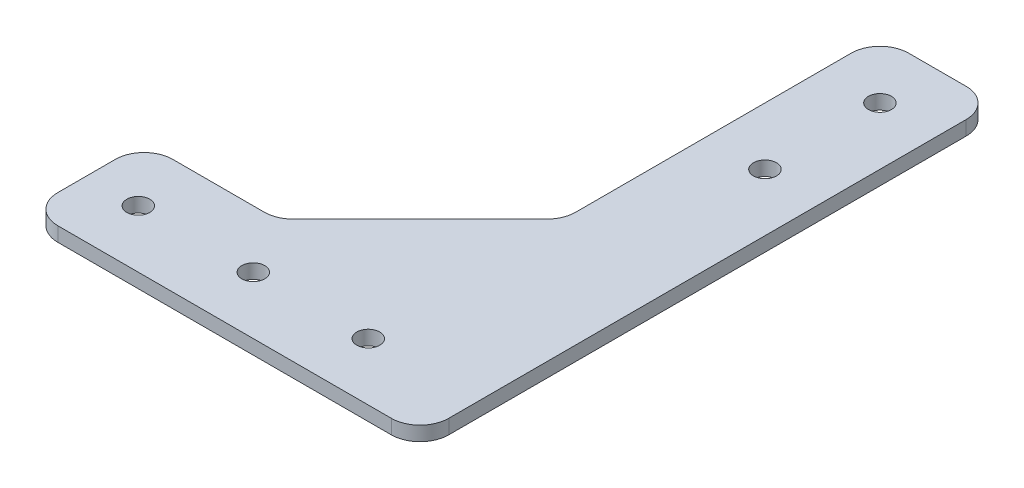
SolidWorks part; units mm, degrees
ref_plane "Front Plane" through (0, 0, 0) normal (0, 0, 1) x (1, 0, 0)
ref_plane "Top Plane" through (0, 0, 0) normal (0, 1, 0) x (1, 0, 0)
ref_plane "Right Plane" through (0, 0, 0) normal (1, 0, 0) x (0, 0, -1)
sketch "Sketch1" plane through (0, 0, 0) normal (0, 1, 0) x (1, 0, 0)
  line L0 (0, -101.6) -> (0, 0)
  line L1 (0, 0) -> (25.4, 0)
  line L2 (0, 0) -> (0, -127) construction
  line L3 (0, -127) -> (25.4, -127)
  line L4 (25.4, 0) -> (25.4, -127)
  line L5 (25.4, -127) -> (-60.96, -127)
  line L6 (25.4, -127) -> (25.4, -101.6)
  line L7 (25.4, -101.6) -> (-60.96, -101.6)
  line L8 (-60.96, -127) -> (-60.96, -101.6)
  line L9 (12.7, 0) -> (12.7, -127) construction
  line L10 (-60.96, -114.3) -> (25.4, -114.3) construction
  line L11 (-49.53, -114.3) -> (-24.13, -114.3) construction
  circle A0 centre (12.7, -12.7) radius 2.54
  circle A1 centre (12.7, -38.1) radius 2.54
  circle A4 centre (-49.53, -114.3) radius 2.54
  circle A7 centre (-24.13, -114.3) radius 2.54
  circle A8 centre (1.27, -114.3) radius 2.54
  circle A10 centre (26.67, -114.3) radius 2.54 [skipped]
  dimension "D9" = 5.08
  dimension "D12" = 5.08
  dimension "D1" = 25.4
  dimension "D2" = 25.4
  dimension "D3" = 127
  dimension "D4" = 86.36
  dimension "D5" = 11.43
  dimension "D6" = 25.4
  dimension "D7" = 12.7
  dimension "D11" = 25.4
  dimension "D10" = 4
extrude "Boss-Extrude1" add sketch "Sketch1" along normal blind 3.175
chamfer "Chamfer1" distance 31.75 angle 45 1 edges at (0, 1.5875, 101.6)
fillet "Fillet1" radius 6.35 7 edges at (25.4, 1.5875, 0) (25.4, 1.5875, 127) (-60.96, 1.5875, 127) (-60.96, 1.5875, 101.6) (0, 1.5875, 69.85) (0, 1.5875, 0) (-31.75, 1.5875, 101.6)
